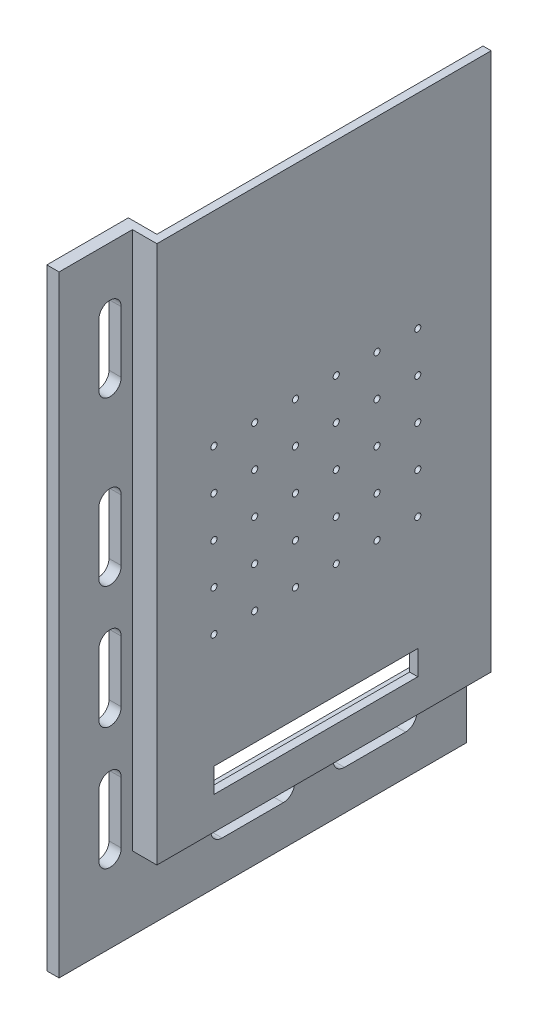
SolidWorks part; units mm, degrees
ref_plane "前视基准面" through (0, 0, 0) normal (0, 0, 1) x (1, 0, 0)
ref_plane "上视基准面" through (0, 0, 0) normal (0, 1, 0) x (1, 0, 0)
ref_plane "右视基准面" through (0, 0, 0) normal (1, 0, 0) x (0, 0, -1)
other "Configuration Table"
sketch "草图1" plane through (0, 0, 0) normal (1, 0, 0) x (0, 0, -1)
  line L0 (12.5, 20) -> (12.5, 35) construction
  line L2 (0, 0) -> (0, 150)
  line L3 (0, 150) -> (18, 150)
  line L4 (18, 18) -> (18, 150)
  line L6 (0, 0) -> (0, 18)
  line L7 (18, 18) -> (100, 18)
  line L8 (100, 0) -> (100, 18)
  line L9 (9.75, 20) -> (9.75, 35)
  line L10 (15.25, 20) -> (15.25, 35)
  line L11 (12.5, 50) -> (12.5, 65) construction
  line L12 (9.75, 50) -> (9.75, 65)
  line L13 (15.25, 50) -> (15.25, 65)
  line L14 (12.5, 80) -> (12.5, 95) construction
  line L15 (9.75, 80) -> (9.75, 95)
  line L16 (15.25, 80) -> (15.25, 95)
  line L17 (12.5, 120) -> (12.5, 135) construction
  line L18 (9.75, 120) -> (9.75, 135)
  line L19 (15.25, 120) -> (15.25, 135)
  line L20 (0, 0) -> (100, 0)
  line L23 (40, 12.5) -> (55, 12.5) construction
  line L24 (40, 15.25) -> (55, 15.25)
  line L25 (40, 9.75) -> (55, 9.75)
  line L26 (70, 12.5) -> (85, 12.5) construction
  line L27 (70, 15.25) -> (85, 15.25)
  line L28 (70, 9.75) -> (85, 9.75)
  arc A0 (9.75, 20) -> (15.25, 20) centre (12.5, 20) ccw
  arc A1 (15.25, 35) -> (9.75, 35) centre (12.5, 35) ccw
  arc A2 (9.75, 50) -> (15.25, 50) centre (12.5, 50) ccw
  arc A3 (15.25, 65) -> (9.75, 65) centre (12.5, 65) ccw
  arc A4 (9.75, 80) -> (15.25, 80) centre (12.5, 80) ccw
  arc A5 (15.25, 95) -> (9.75, 95) centre (12.5, 95) ccw
  arc A6 (9.75, 120) -> (15.25, 120) centre (12.5, 120) ccw
  arc A7 (15.25, 135) -> (9.75, 135) centre (12.5, 135) ccw
  arc A10 (40, 15.25) -> (40, 9.75) centre (40, 12.5) ccw
  arc A11 (55, 9.75) -> (55, 15.25) centre (55, 12.5) ccw
  arc A12 (70, 15.25) -> (70, 9.75) centre (70, 12.5) ccw
  arc A13 (85, 9.75) -> (85, 15.25) centre (85, 12.5) ccw
  point P10 (12.5, 27.5)
  point P15 (12.5, 57.5)
  point P22 (12.5, 87.5)
  point P29 (12.5, 127.5)
  point P38 (32.1505, 12.5)
  point P43 (47.5, 12.5)
  point P50 (77.5, 12.5)
  dimension "D1" = 150
  dimension "D2" = 100
  dimension "D3" = 18
  dimension "D4" = 18
  dimension "D5" = 5.5
  dimension "D6" = 5.5
  dimension "D7" = 15
  dimension "D8" = 15
  dimension "D9" = 25
  dimension "D10" = 15
  dimension "D11" = 5.5
  dimension "D12" = 15
  dimension "D13" = 15
  dimension "D14" = 5.5
  dimension "D15" = 15
  dimension "D16" = 15
  dimension "D17" = 5.5
  dimension "D18" = 5.5
  dimension "D19" = 15
  dimension "D20" = 15
  dimension "D21" = 15
  dimension "D22" = 15
  dimension "D23" = 5.5
  dimension "D24" = 5.5
extrude "凸台-拉伸1" add sketch "草图1" along normal blind 3 contours L2 L20 L8 L7 L4 L3 A13 L28 A12 L27 A11 L25 A10 L24 A7 L19 A6 L18 A5 L16 A4 L15 A3 L13 A2 L12 A1 L10 A0 L9
sketch "草图2" plane through (3, 0, 0) normal (1, 0, 0) x (0, 0, -1)
  line L0 (18, 18) -> (100, 18) construction
  line L1 (18, 150) -> (20, 150)
  line L2 (18, 150) -> (18, 18)
  line L3 (18, 18) -> (20, 18)
  line L4 (20, 150) -> (20, 20)
  line L6 (100, 18) -> (20, 18)
  line L7 (100, 18) -> (100, 20)
  line L8 (100, 20) -> (20, 20)
  dimension "D1" = 2
  dimension "D2" = 2
extrude "凸台-拉伸2" add sketch "草图2" along normal blind 6 separate body
sketch "草图4" plane through (3, 0, 0) normal (-1, 0, 0) x (0, 0, 1)
  line L6 (-18, 18) -> (-18, 150)
  line L7 (-18, 150) -> (-20, 150)
  line L8 (-20, 150) -> (-20, 20)
  line L9 (-20, 20) -> (-100, 20)
  line L10 (-100, 20) -> (-100, 18)
  line L11 (-100, 18) -> (-18, 18)
  line L12 (-18, 18) -> (-18, 150)
  line L13 (-18, 150) -> (-20, 150)
  line L14 (-20, 150) -> (-20, 20)
  line L15 (-20, 20) -> (-100, 20)
  line L16 (-100, 20) -> (-100, 18)
  line L17 (-100, 18) -> (-18, 18)
  dimension "D1" = 0
extrude "凸台-拉伸3" add sketch "草图4" along normal blind 3
sketch "草图5" plane through (0, 20, 0) normal (0, 1, 0) x (1, 0, 0)
  line L0 (0, 20) -> (9, 20) construction
  line L1 (9, 100) -> (7, 100)
  line L2 (9, 100) -> (9, 20)
  line L3 (9, 20) -> (7, 20)
  line L4 (7, 100) -> (7, 20)
  dimension "D1" = 2
extrude "凸台-拉伸4" add sketch "草图5" along normal blind 130
sketch "草图6" plane through (7, 0, 0) normal (-1, 0, 0) x (0, 0, 1)
  line L0 (-100, 20) -> (-20, 20) construction
  line L1 (-82, 26) -> (-32, 26)
  line L2 (-82, 26) -> (-82, 32)
  line L3 (-82, 32) -> (-32, 32)
  line L4 (-32, 26) -> (-32, 32)
  line L5 (-100, 150) -> (-100, 20) construction
  dimension "D1" = 50
  dimension "D2" = 6
  dimension "D3" = 6
  dimension "D4" = 18
extrude "切除-拉伸1" cut sketch "草图6" against normal blind 130
sketch "草图7" plane through (7, 0, 0) normal (-1, 0, 0) x (0, 0, 1)
  line L1 (-79.0213, 121.8702) -> (-93.4923, 121.8702)
  line L2 (-79.0213, 121.8702) -> (-79.0213, 143.0201)
  line L3 (-79.0213, 143.0201) -> (-93.4923, 143.0201)
  line L4 (-93.4923, 121.8702) -> (-93.4923, 143.0201)
  line L5 (-41.7306, 121.8702) -> (-26.332, 121.8702)
  line L6 (-41.7306, 121.8702) -> (-41.7306, 143.0201)
  line L7 (-41.7306, 143.0201) -> (-26.332, 143.0201)
  line L8 (-26.332, 121.8702) -> (-26.332, 143.0201)
  line L9 (-93.4923, 29.1073) -> (-83.4739, 29.1073)
  line L10 (-93.4923, 29.1073) -> (-93.4923, 49.3296)
  line L11 (-93.4923, 49.3296) -> (-83.4739, 49.3296)
  line L12 (-83.4739, 29.1073) -> (-83.4739, 49.3296)
  line L13 (-30.0425, 27.0665) -> (-24.1057, 27.0665)
  line L14 (-30.0425, 27.0665) -> (-30.0425, 49.3296)
  line L15 (-30.0425, 49.3296) -> (-24.1057, 49.3296)
  line L16 (-24.1057, 27.0665) -> (-24.1057, 49.3296)
extrude "凸台-拉伸5" add sketch "草图7" along normal blind 2
sketch "草图8" plane through (7, 0, 0) normal (-1, 0, 0) x (0, 0, 1)
  line L0 (-100, 150) -> (-100, 20) construction
  line L1 (-20, 20) -> (-100, 20) construction
  circle A0 centre (-82, 100) radius 0.75
  dimension "D1" = 1.5
  dimension "D2" = 18
  dimension "D3" = 80
extrude "切除-拉伸2" cut sketch "草图8" against normal blind 2
pattern_linear "阵列(线性)1" count 5 spacing 10 along (0, -1, 0) count 6 spacing 10 along (0, 0, 1) of "切除-拉伸2"
